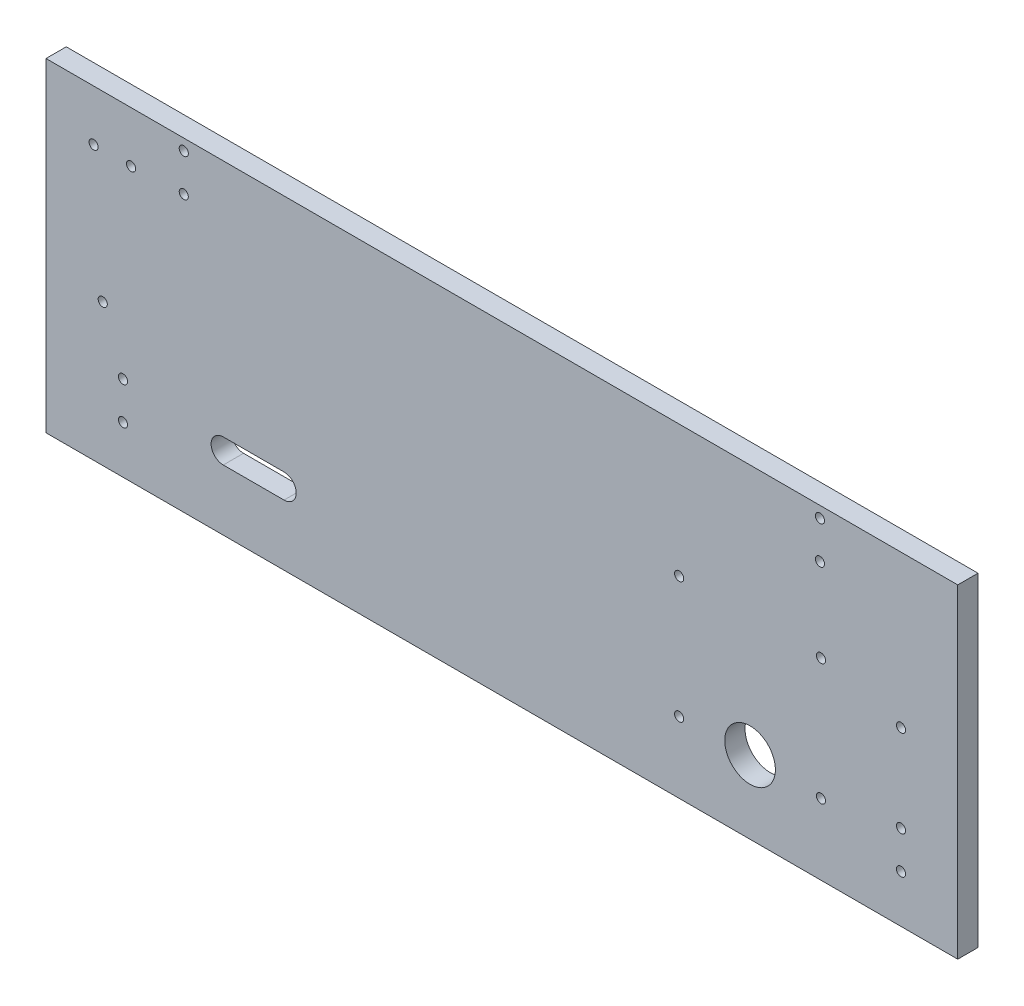
SolidWorks part; units mm, degrees
material "Multistrato di pioppo"
ref_plane "Piano frontale" through (0, 0, 0) normal (0, 0, 1) x (1, 0, 0)
ref_plane "Piano superiore" through (0, 0, 0) normal (0, 1, 0) x (1, 0, 0)
ref_plane "Piano destro" through (0, 0, 0) normal (1, 0, 0) x (0, 0, -1)
sketch "Schizzo1" plane through (0, 0, 0) normal (0, 0, 1) x (1, 0, 0)
  line L1 (0, 0) -> (450, 0)
  line L2 (0, 0) -> (0, 160)
  line L3 (0, 160) -> (450, 160)
  line L4 (450, 0) -> (450, 160)
  dimension "D1" = 450
  dimension "D2" = 160
extrude "Estrusione-Estrusione1" add sketch "Schizzo1" along normal blind 10
sketch "Schizzo2" plane through (0, 0, 10) normal (0, 0, 1) x (1, 0, 0)
  line L0 (102.5, 36) -> (347.5, 36) construction
  line L1 (225, 0) -> (225, 36) construction
  line L2 (0, 0) -> (450, 0) construction
  line L3 (87.5, 36) -> (117.5, 36) construction
  line L4 (87.5, 42) -> (117.5, 42)
  line L5 (87.5, 30) -> (117.5, 30)
  circle A1 centre (347.5, 36) radius 12.5
  arc A2 (87.5, 42) -> (87.5, 30) centre (87.5, 36) ccw
  arc A3 (117.5, 30) -> (117.5, 42) centre (117.5, 36) ccw
  circle A8 centre (68, 154.5) radius 2.25
  circle A9 centre (68, 136) radius 2.25
  circle A10 centre (382, 154.5) radius 2.25
  circle A11 centre (382, 136) radius 2.25
  circle A12 centre (38, 42) radius 2.25
  circle A13 centre (38, 23.5) radius 2.25
  circle A14 centre (422, 42) radius 2.25
  circle A15 centre (422, 23.5) radius 2.25
  circle A16 centre (23.5, 134.9337) radius 2.25
  circle A17 centre (42, 134.9337) radius 2.25
  circle A18 centre (28, 70) radius 2.25
  circle A19 centre (422, 85) radius 2.25
  circle A20 centre (312.5, 95) radius 2.25
  circle A21 centre (382.5, 95) radius 2.25
  circle A22 centre (382.5, 35) radius 2.25
  circle A23 centre (312.5, 35) radius 2.25
  point P9 (102.5, 36)
  dimension "D2" = 25
  dimension "D3" = 12
  dimension "D5" = 30
  dimension "D6" = 4.5
  dimension "D17" = 4.5
  dimension "D18" = 4.5
  dimension "D1" = 36
  dimension "D4" = 245
extrude "Taglio-Estrusione1" cut sketch "Schizzo2" against normal blind 10
